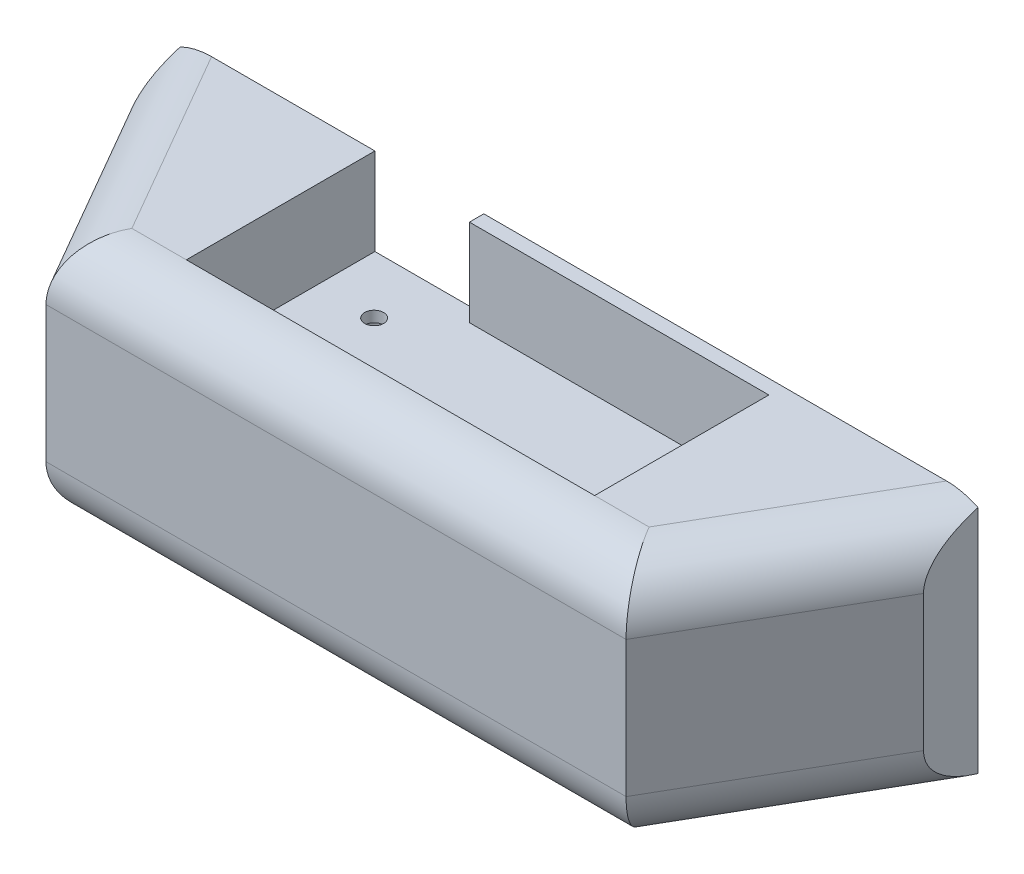
SolidWorks part; units mm, degrees
material "ABS"
ref_plane "Alzado" through (0, 0, 0) normal (0, 0, 1) x (1, 0, 0)
ref_plane "Planta" through (0, 0, 0) normal (0, 1, 0) x (1, 0, 0)
ref_plane "Vista lateral" through (0, 0, 0) normal (1, 0, 0) x (0, 0, -1)
sketch "Sketch2" plane through (0, 0, 0) normal (0, 1, 0) x (1, 0, 0)
  line L0 (-73.275, 22.3205) -> (73.275, 22.3205)
  line L1 (73.275, 22.3205) -> (73.275, 12.3205)
  line L2 (73.275, 12.3205) -> (53.275, -22.3205)
  line L3 (53.275, -22.3205) -> (-53.275, -22.3205)
  line L4 (-53.275, -22.3205) -> (-73.275, 12.3205)
  line L5 (-73.275, 12.3205) -> (-73.275, 22.3205)
  line L6 (0, 22.3205) -> (0, -22.3205) construction
  dimension "D1" = 10
  dimension "D2" = 40
  dimension "D3" = 120
  dimension "D4" = 106.55
extrude "Boss-Extrude2" add sketch "Sketch2" along normal blind 45
fillet "Fillet2" radius 10 3 edges at (63.275, 45, 5) (0, 45, 22.3205) (-63.275, 45, 5)
fillet "Fillet3" radius 10 3 edges at (-63.275, 0, 5) (63.275, 0, 5) (0, 0, 22.3205)
sketch "Sketch3" plane through (0, 45, 0) normal (0, 1, 0) x (1, 0, 0)
  line L5 (0, -12.3205) -> (0, 22.3205) construction
  line L6 (-47.5015, -12.3205) -> (47.5015, -12.3205) construction
  line L7 (67.5015, 22.3205) -> (-67.5015, 22.3205) construction
  line L8 (-37.5, -12.3205) -> (37.5, -12.3205)
  line L9 (-37.5, -12.3205) -> (-37.5, 19.6795)
  line L10 (-37.5, 19.6795) -> (37.5, 19.6795)
  line L11 (37.5, -12.3205) -> (37.5, 19.6795)
  point P4 (0, 19.6795)
  dimension "D1" = 75
  dimension "D2" = 32
  dimension "D3" = 2.641
sketch "Sketch6" plane through (0, 0, 0) normal (0, -1, 0) x (-1, 0, 0)
  line L0 (0, -12.3205) -> (0, 22.3205) construction
  line L1 (-47.5015, -12.3205) -> (47.5015, -12.3205) construction
  line L2 (-67.5015, 22.3205) -> (67.5015, 22.3205) construction
  circle A0 centre (40, -2.3205) radius 1.5
  circle A1 centre (-40, -2.3205) radius 1.5
  circle A2 centre (60, 17.6795) radius 1.5
  circle A3 centre (-60, 17.6795) radius 1.5
  dimension "D1" = 40
  dimension "D3" = 3
  dimension "D4" = 60
  dimension "D2" = 10
  dimension "D5" = 30
sketch "Sketch7" plane through (0, 0, 0) normal (0, -1, 0) x (-1, 0, 0)
  line L0 (0, -12.3205) -> (0, 22.3205) construction
  line L1 (-47.5015, -12.3205) -> (47.5015, -12.3205) construction
  line L2 (-67.5015, 22.3205) -> (67.5015, 22.3205) construction
  circle A0 centre (40, 7.6795) radius 1.5
  circle A1 centre (-40, 7.6795) radius 1.5
  dimension "D1" = 3
  dimension "D2" = 40
  dimension "D3" = 20
extrude "Cut-Extrude5" cut sketch "Sketch6" against normal blind 10
extrude "Cut-Extrude6" cut sketch "Sketch7" against normal blind 10
sketch "Sketch9" plane through (0, 0, 0) normal (0, -1, 0) x (-1, 0, 0)
  line L0 (0, -12.3205) -> (0, 22.3205) construction
  line L2 (27, 11.6795) -> (0, 11.6795) construction
  line L3 (27, 7.1795) -> (23.5744, 7.1795)
  line L4 (27, 16.1795) -> (23.5744, 16.1795)
  line L5 (0, -12.3205) -> (0, 35.6795) construction
  line L6 (-27, 16.1795) -> (-23.5744, 16.1795)
  line L7 (-27, 7.1795) -> (-23.5744, 7.1795)
  arc A1 (27, 7.1795) -> (27, 16.1795) centre (27, 11.6795) ccw
  arc A2 (-27, 7.1795) -> (-27, 16.1795) centre (-27, 11.6795) cw
  arc A3 (-23.5744, 7.1795) -> (23.5744, 7.1795) centre (0, 11.6795) ccw
  arc A4 (23.5744, 16.1795) -> (-23.5744, 16.1795) centre (0, 11.6795) ccw
  point P4 (0, 0)
  point P14 (0, 0)
  dimension "D3" = 9
  dimension "D2" = 27
extrude "Cut-Extrude7" cut sketch "Sketch9" against normal blind 27
extrude "Cut-Extrude8" cut sketch "Sketch3" against normal offset from surface (16 mm away) 2 up to face at (0, 27, -11.8717)
sketch "Sketch11" plane through (0, 29, 0) normal (0, 1, 0) x (1, 0, 0)
  line L0 (0, -12.3205) -> (0, 22.3205) construction
  line L3 (-21.5121, 22.3205) -> (21.5121, 22.3205) construction
  line L5 (27, 11.6795) -> (-27, 11.6795) construction
  circle A0 centre (27, 11.6795) radius 1.75
  arc A1 (27, 7.1795) -> (27, 16.1795) centre (27, 11.6795) ccw construction
  circle A2 centre (-27, 11.6795) radius 1.75
  point P9 (0, 11.6795)
  dimension "D1" = 3.5
extrude "Cut-Extrude9" cut sketch "Sketch11" against normal blind 20
sketch "Sketch12" plane through (0, 45, 0) normal (0, 1, 0) x (1, 0, 0)
  line L6 (0, -12.3205) -> (0, 22.3205) construction
  line L7 (-37.5, -12.3205) -> (37.5, -12.3205) construction
  line L8 (67.5015, 22.3205) -> (-67.5015, 22.3205) construction
  line L9 (-37.5, 19.6795) -> (-17.5, 19.6795)
  line L10 (-37.5, 19.6795) -> (-37.5, 22.3205)
  line L11 (-37.5, 22.3205) -> (-17.5, 22.3205)
  line L12 (-17.5, 19.6795) -> (-17.5, 22.3205)
  dimension "D1" = 20
extrude "Cut-Extrude11" cut sketch "Sketch12" against normal up to surface (16 mm away) up to face at (-27, 29, -13.4295)
